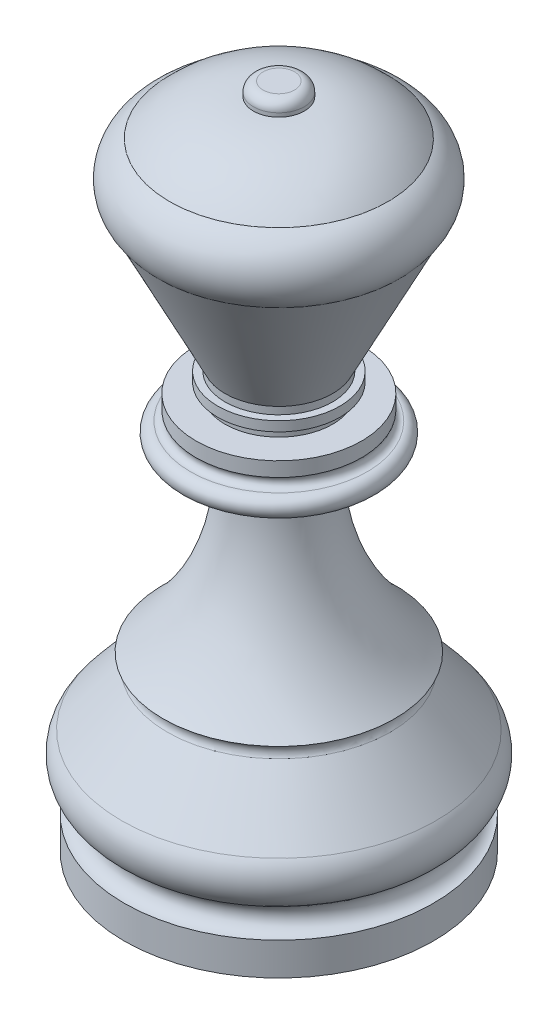
SolidWorks part; units mm, degrees
ref_plane "Ön Düzlem" through (0, 0, 0) normal (0, 0, 1) x (1, 0, 0)
ref_plane "Üst Düzlem" through (0, 0, 0) normal (0, 1, 0) x (1, 0, 0)
ref_plane "Sağ Düzlem" through (0, 0, 0) normal (1, 0, 0) x (0, 0, -1)
sketch "Çizim1" plane through (0, 0, 0) normal (0, 0, 1) x (1, 0, 0)
  line L0 (-8.5194, -30.9411) -> (7.4806, -30.9411)
  line L1 (7.4806, -30.9411) -> (7.4806, -27.5523)
  line L2 (-8.5194, -30.9411) -> (-8.5194, 35.5589)
  line L3 (3.9301, 26.6095) -> (-2.9547, 12.8991)
  line L4 (-2.9547, 12.8991) -> (-2.9547, 12.1491)
  line L5 (-2.9547, 12.1491) -> (-2.2047, 12.1491)
  line L6 (-2.2047, 12.1491) -> (-2.2047, 11.1491)
  line L7 (-2.2047, 11.1491) -> (-2.9547, 11.1491)
  line L8 (-2.9547, 11.1491) -> (-2.9547, 10.1491)
  line L9 (-2.9547, 10.1491) -> (0.0453, 10.1491)
  line L10 (0.0453, 10.1491) -> (0.0453, 8.6491)
  line L11 (0.6218, 5.649) -> (-3.6205, 5.649)
  line L12 (-8.5194, 57.1011) -> (-8.5194, -57.1011) construction
  line L14 (3.0274, -14.4472) -> (7.7493, -20.0217)
  line L19 (-5.889, 36.7427) -> (-5.889, 38.1349)
  line L20 (-5.889, 38.1349) -> (-8.5194, 38.1349)
  line L21 (-8.5194, 38.1349) -> (-8.5194, 35.5589)
  arc A0 (3.9301, 26.6095) -> (2.793, 32.9783) centre (1.0453, 29.3804) ccw
  arc A1 (-3.6205, 5.649) -> (3.4675, -13.0266) centre (18.6209, 3.4075) ccw
  arc A2 (6.8247, -24.9762) -> (7.4806, -27.5523) centre (7.4811, -26.1806) ccw
  arc A3 (6.8247, -24.9762) -> (7.7493, -20.0217) centre (5.2693, -22.1224) ccw
  arc A4 (3.4675, -13.0266) -> (3.0274, -14.4472) centre (3.7382, -13.8889) ccw
  arc A5 (0.6218, 5.649) -> (0.6218, 7.6791) centre (0.6218, 6.6641) ccw
  arc A6 (0.0453, 8.6491) -> (0.6218, 7.6791) centre (0.5719, 8.3058) ccw
  arc A7 (2.793, 32.9783) -> (-5.889, 36.7427) centre (-5.8888, 24.849) ccw
  dimension "D9" = 4
  dimension "D1" = 16
  dimension "D2" = 0.75
  dimension "D3" = 0.75
  dimension "D4" = 1
  dimension "D5" = 0.75
  dimension "D6" = 1
  dimension "D7" = 1.5
  dimension "D8" = 3
  dimension "D10" = 4
revolve "Döndür1" add sketch "Çizim1" angle 360 about L12
fillet "Radyus1" radius 1 1 edges at (-8.5194, 38.1349, 2.6305)
